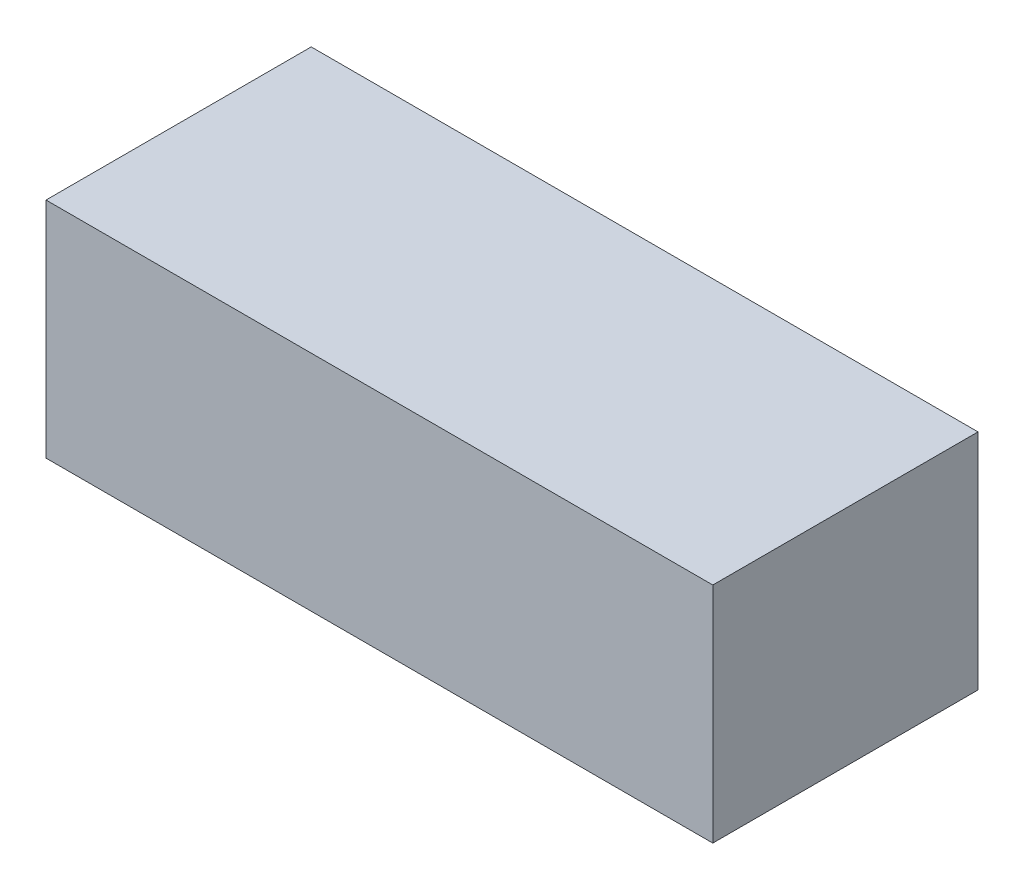
SolidWorks part; units mm, degrees
material "Natural Rubber"
ref_plane "Front Plane" through (0, 0, 0) normal (0, 0, 1) x (1, 0, 0)
ref_plane "Top Plane" through (0, 0, 0) normal (0, 1, 0) x (1, 0, 0)
ref_plane "Right Plane" through (0, 0, 0) normal (1, 0, 0) x (0, 0, -1)
sketch "Sketch1" plane through (0, 0, 0) normal (0, 1, 0) x (1, 0, 0)
  line L1 (88, -35) -> (-88, -35)
  line L2 (88, -35) -> (88, 35)
  line L3 (88, 35) -> (-88, 35)
  line L4 (-88, -35) -> (-88, 35)
  line L5 (88, -35) -> (-88, 35) construction
  line L6 (88, 35) -> (-88, -35) construction
  point P0 (0, 0)
  dimension "D1" = 176
  dimension "D2" = 70
extrude "Boss-Extrude1" add sketch "Sketch1" along normal blind 59
